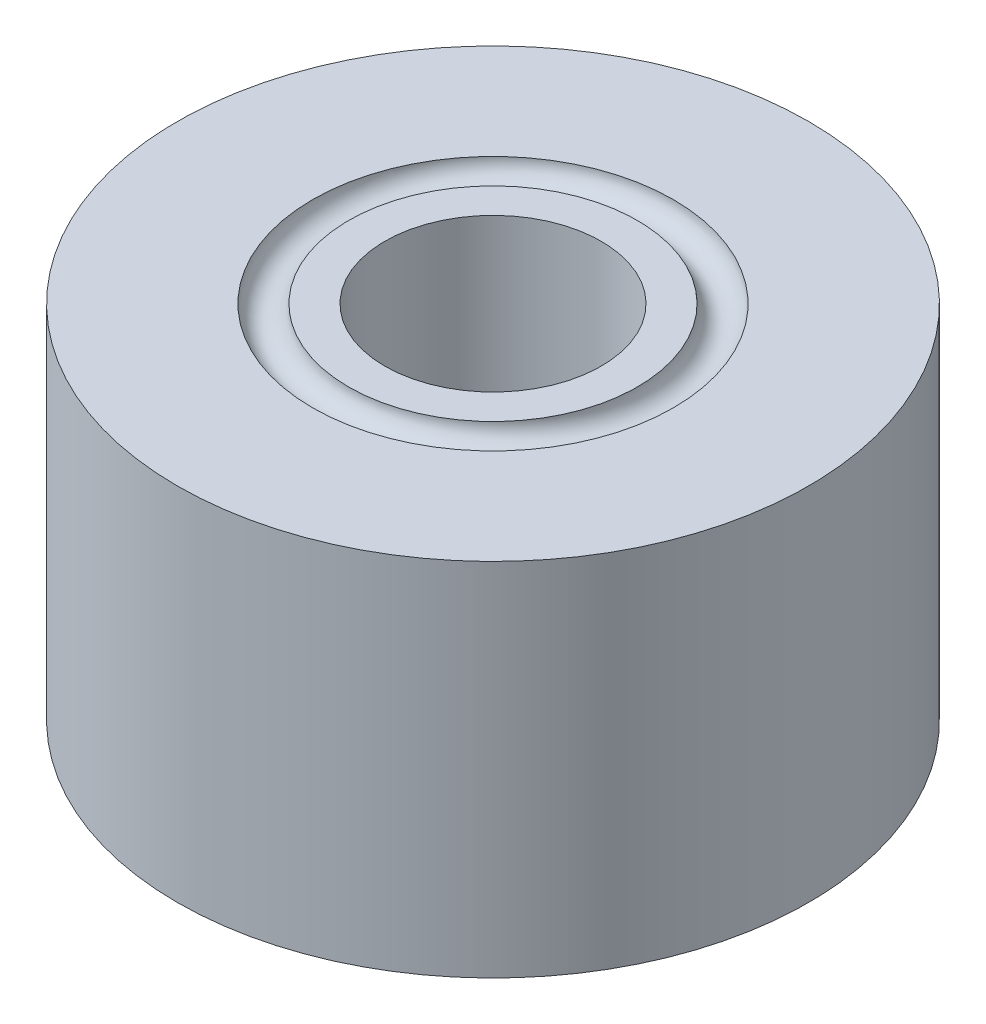
SolidWorks part; units mm, degrees
ref_plane "Front Plane" through (0, 0, 0) normal (0, 0, 1) x (1, 0, 0)
ref_plane "Top Plane" through (0, 0, 0) normal (0, 1, 0) x (1, 0, 0)
ref_plane "Right Plane" through (0, 0, 0) normal (1, 0, 0) x (0, 0, -1)
sketch "Sketch2" plane through (0, 0, 0) normal (0, 1, 0) x (1, 0, 0)
  circle A0 centre (0, 0) radius 17.5
  dimension "D1" = 35
extrude "Boss-Extrude1" add sketch "Sketch2" along normal blind 20 contours A0
sketch "Sketch39" plane through (0, 20, 0) normal (0, 1, 0) x (1, 0, 0)
  circle A0 centre (0, 0) radius 9
  dimension "D1" = 18
sweep "Cut-Sweep1" cut path "Sketch39" circular profile diameter 2 parameters "D3"=2
sketch "Sketch62" plane through (0, 0, 0) normal (0, 1, 0) x (1, 0, 0)
  circle A0 centre (0, 0) radius 2.5
  dimension "D1" = 5
extrude "Cut-Extrude3" cut sketch "Sketch62" along normal through all
sketch "Sketch65" plane through (0, 20, 0) normal (0, 1, 0) x (1, 0, 0)
  circle A0 centre (0, 0) radius 6
  dimension "D1" = 12
extrude "Cut-Extrude4" cut sketch "Sketch65" against normal blind 11
